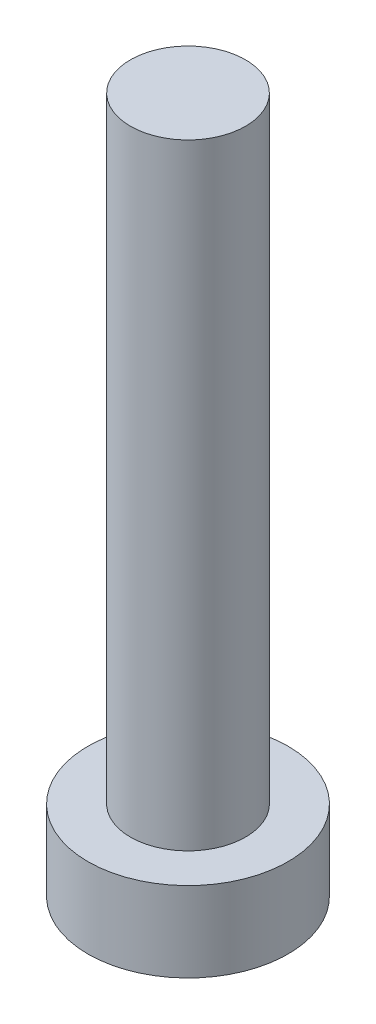
SolidWorks part; units mm, degrees
ref_plane "Front Plane" through (0, 0, 0) normal (0, 0, 1) x (1, 0, 0)
ref_plane "Top Plane" through (0, 0, 0) normal (0, 1, 0) x (1, 0, 0)
ref_plane "Right Plane" through (0, 0, 0) normal (1, 0, 0) x (0, 0, -1)
sketch "Sketch1" plane through (0, 0, 0) normal (0, 1, 0) x (1, 0, 0)
  circle A0 centre (0, 0) radius 4.1275
  dimension "D1" = 8.255
extrude "Boss-Extrude1" add sketch "Sketch1" along normal blind 3.302
sketch "Sketch2" plane through (0, 3.302, 0) normal (0, 1, 0) x (1, 0, 0)
  circle A0 centre (0, 0) radius 2.3749
  dimension "D1" = 4.7498
extrude "Boss-Extrude2" add sketch "Sketch2" along normal blind 25.4
